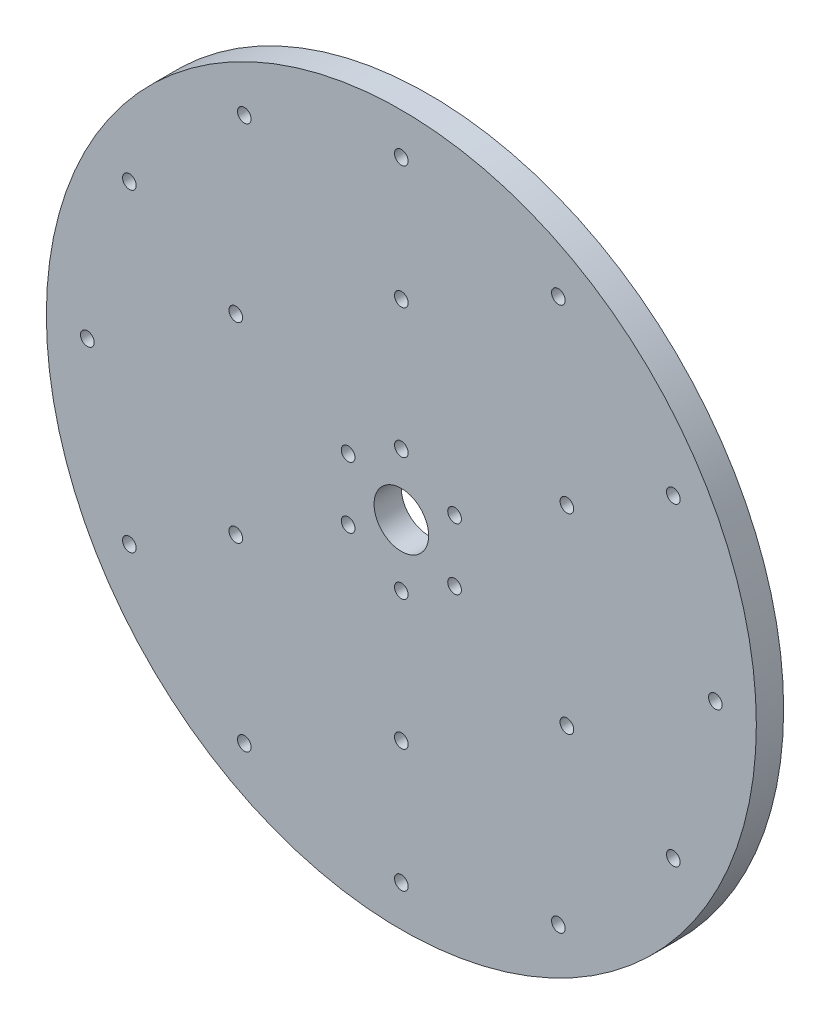
SolidWorks part; units mm, degrees
material "Thornel Mat VMA"
ref_plane "前视基准面" through (0, 0, 0) normal (0, 0, 1) x (1, 0, 0)
ref_plane "上视基准面" through (0, 0, 0) normal (0, 1, 0) x (1, 0, 0)
ref_plane "右视基准面" through (0, 0, 0) normal (1, 0, 0) x (0, 0, -1)
other "Configuration Table"
sketch "草图1" plane through (0, 0, 0) normal (0, 0, 1) x (1, 0, 0)
  circle A0 centre (0, 0) radius 130
  dimension "D1" = 260
extrude "凸台-拉伸1" add sketch "草图1" along normal blind 10
sketch "草图4" plane through (0, 0, 0) normal (0, 0, -1) x (-1, 0, 0)
  circle A0 centre (0, 0) radius 17.5
  dimension "D1" = 35
extrude "切除-拉伸1" [suppressed] cut sketch "草图4" against normal blind 10
sketch "草图5" plane through (0, 0, 0) normal (0, 0, -1) x (-1, 0, 0)
  circle A0 centre (0, 0) radius 13.5 construction
  circle A1 centre (0, 13.5) radius 1.5
  circle A2 centre (11.6913, 6.75) radius 1.5
  circle A3 centre (11.6913, -6.75) radius 1.5
  circle A4 centre (0, -13.5) radius 1.5
  circle A5 centre (-11.6913, -6.75) radius 1.5
  circle A6 centre (-11.6913, 6.75) radius 1.5
  point P17 (0, 0)
  dimension "D1" = 27
  dimension "D2" = 3
  dimension "D3" = 6
extrude "切除-拉伸2" [suppressed] cut sketch "草图5" against normal blind 10
sketch "草图7" plane through (0, 0, 0) normal (0, 0, -1) x (-1, 0, 0)
  line L0 (57.5, 99.5929) -> (0, 0) construction
  line L1 (0, 0) -> (0, 115) construction
  circle A0 centre (0, 0) radius 70 construction
  circle A1 centre (0, 0) radius 115 construction
  circle A2 centre (0, 70) radius 2.5
  circle A3 centre (60.6218, 35) radius 2.5
  circle A4 centre (60.6218, -35) radius 2.5
  circle A5 centre (0, -70) radius 2.5
  circle A6 centre (-60.6218, -35) radius 2.5
  circle A7 centre (-60.6218, 35) radius 2.5
  circle A8 centre (57.5, 99.5929) radius 2.5
  circle A9 centre (99.5929, 57.5) radius 2.5
  circle A10 centre (115, 0) radius 2.5
  circle A11 centre (99.5929, -57.5) radius 2.5
  circle A12 centre (57.5, -99.5929) radius 2.5
  circle A13 centre (0, -115) radius 2.5
  circle A14 centre (-57.5, -99.5929) radius 2.5
  circle A15 centre (-99.5929, -57.5) radius 2.5
  circle A16 centre (-115, 0) radius 2.5
  circle A17 centre (-99.5929, 57.5) radius 2.5
  circle A18 centre (-57.5, 99.5929) radius 2.5
  circle A19 centre (0, 115) radius 2.5
  point P18 (0, 0)
  point P32 (0, 0)
  dimension "D1" = 140
  dimension "D2" = 230
  dimension "D3" = 5
  dimension "D5" = 30
  dimension "D6" = 5
  dimension "D4" = 6
  dimension "D7" = 12
extrude "切除-拉伸3" cut sketch "草图7" against normal blind 10
sketch "草图8" [suppressed] plane through (0, 0, 10) normal (0, 0, 1) x (1, 0, 0)
  circle A0 centre (0, 0) radius 40 construction
  circle A1 centre (0, 40) radius 2.5
  circle A2 centre (28.2843, 28.2843) radius 2.5
  circle A3 centre (40, 0) radius 2.5
  circle A4 centre (28.2843, -28.2843) radius 2.5
  circle A5 centre (0, -40) radius 2.5
  circle A6 centre (-28.2843, -28.2843) radius 2.5
  circle A7 centre (-40, 0) radius 2.5
  circle A8 centre (-28.2843, 28.2843) radius 2.5
  point P21 (0, 0)
  dimension "D1" = 80
  dimension "D2" = 5
  dimension "D3" = 8
extrude "切除-拉伸4" [suppressed] cut sketch "草图8" against normal through all
sketch "草图9" plane through (0, 0, 10) normal (0, 0, 1) x (1, 0, 0)
  circle A0 centre (0, 0) radius 10
  dimension "D1" = 20
extrude "切除-拉伸5" cut sketch "草图9" against normal through all
sketch "草图10" plane through (0, 0, 10) normal (0, 0, 1) x (1, 0, 0)
  circle A0 centre (0, 0) radius 22.5 construction
  circle A1 centre (0, 22.5) radius 2.5
  circle A2 centre (19.4856, 11.25) radius 2.5
  circle A3 centre (19.4856, -11.25) radius 2.5
  circle A4 centre (0, -22.5) radius 2.5
  circle A5 centre (-19.4856, -11.25) radius 2.5
  circle A6 centre (-19.4856, 11.25) radius 2.5
  point P17 (0, 0)
  dimension "D1" = 45
  dimension "D2" = 5
  dimension "D3" = 6
extrude "切除-拉伸6" cut sketch "草图10" against normal through all
